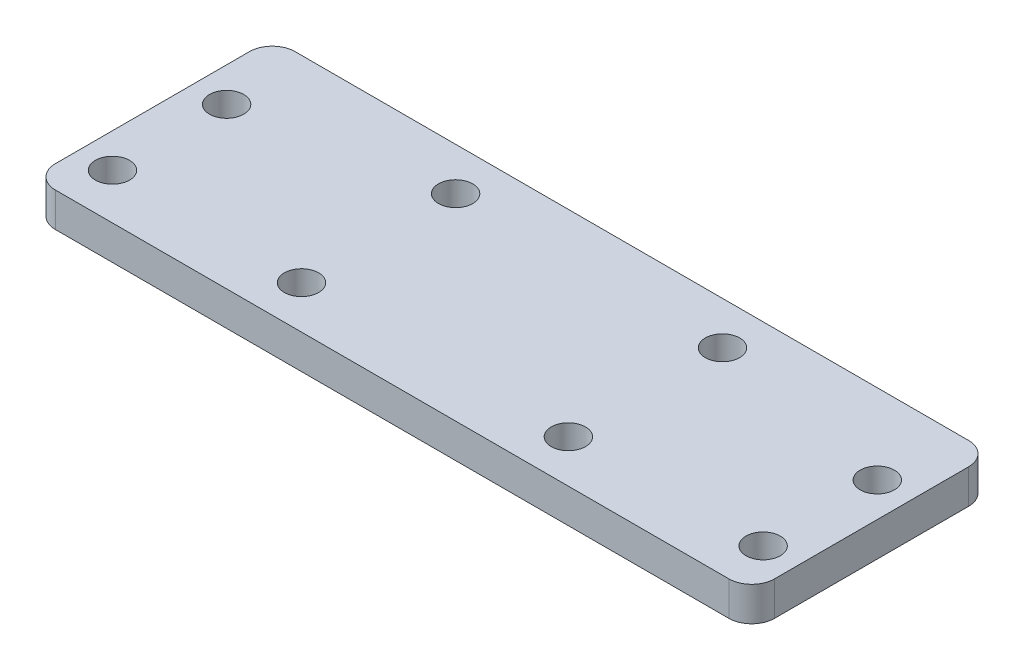
SolidWorks part; units mm, degrees
material "A-玻璃纤维"
ref_plane "前视基准面" through (0, 0, 0) normal (0, 0, 1) x (1, 0, 0)
ref_plane "上视基准面" through (0, 0, 0) normal (0, 1, 0) x (1, 0, 0)
ref_plane "右视基准面" through (0, 0, 0) normal (1, 0, 0) x (0, 0, -1)
other "Configuration Table"
sketch "草图1" plane through (0, 0, 0) normal (0, 1, 0) x (1, 0, 0)
  line L1 (-31.5, -10.5) -> (31.5, -10.5)
  line L2 (-31.5, -10.5) -> (-31.5, 10.5)
  line L3 (-31.5, 10.5) -> (31.5, 10.5)
  line L4 (31.5, -10.5) -> (31.5, 10.5)
  line L5 (-31.5, -10.5) -> (31.5, 10.5) construction
  line L6 (-31.5, 10.5) -> (31.5, -10.5) construction
  line L7 (-11.69, 6.75) -> (11.69, 6.75) construction
  line L8 (-11.69, 6.75) -> (-11.69, -6.75) construction
  line L9 (-11.69, -6.75) -> (11.69, -6.75) construction
  line L10 (11.69, 6.75) -> (11.69, -6.75) construction
  line L11 (-11.69, 6.75) -> (11.69, -6.75) construction
  line L12 (-11.69, -6.75) -> (11.69, 6.75) construction
  circle A0 centre (-11.69, 6.75) radius 1.5
  circle A1 centre (11.69, 6.75) radius 1.5
  circle A2 centre (11.69, -6.75) radius 1.5
  circle A3 centre (-11.69, -6.75) radius 1.5
  point P0 (0, 0)
  point P6 (0, 0)
  dimension "D5" = 3
  dimension "D1" = 21
  dimension "D2" = 63
  dimension "D3" = 13.5
  dimension "D4" = 23.38
extrude "凸台-拉伸1" add sketch "草图1" along normal blind 3
fillet "圆角1" radius 2 4 edges at (-31.5, 1.5, 10.5) (-31.5, 1.5, -10.5) (31.5, 1.5, -10.5) (31.5, 1.5, 10.5)
sketch "草图3" plane through (0, 3, 0) normal (0, 1, 0) x (1, 0, 0)
  line L0 (-31.5, 8.5) -> (-31.5, -8.5) construction
  line L1 (-29.5, -10.5) -> (29.5, -10.5) construction
  line L2 (-28.5, 3.5) -> (-28.5, -6.5) construction
  line L3 (0, -10.5) -> (0, 10.5) construction
  line L4 (29.5, 10.5) -> (-29.5, 10.5) construction
  circle A0 centre (-28.5, -6.5) radius 1.5
  circle A1 centre (-28.5, 3.5) radius 1.5
  circle A2 centre (28.5, -6.5) radius 1.5
  circle A3 centre (28.5, 3.5) radius 1.5
  point P14 (0, 0)
  dimension "D2" = 3
  dimension "D1" = 10
  dimension "D3" = 3
  dimension "D4" = 4
extrude "切除-拉伸2" cut sketch "草图3" against normal through all
